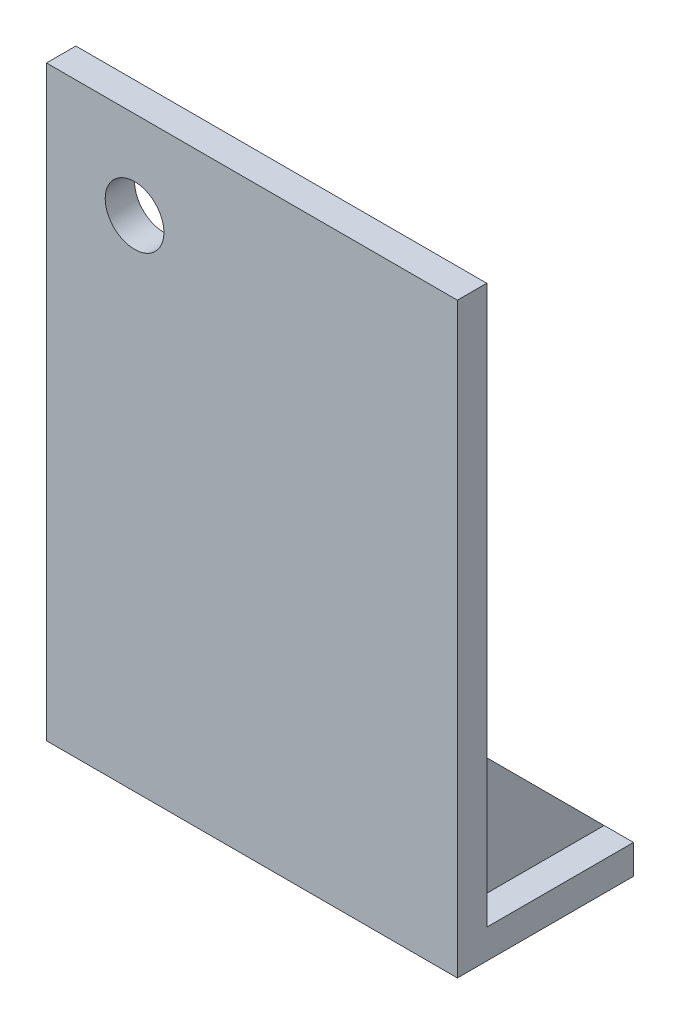
SolidWorks part; units mm, degrees
ref_plane "Front Plane" through (0, 0, 0) normal (0, 0, 1) x (1, 0, 0)
ref_plane "Top Plane" through (0, 0, 0) normal (0, 1, 0) x (1, 0, 0)
ref_plane "Right Plane" through (0, 0, 0) normal (1, 0, 0) x (0, 0, -1)
sketch "Sketch1" plane through (0, 0, 0) normal (0, 0, 1) x (1, 0, 0)
  line L0 (0, -15) -> (6.6093, -15) construction
  line L1 (5, 0) -> (70, 0)
  line L2 (0, -5) -> (0, -25)
  line L3 (5, -30) -> (40, -30)
  line L4 (70, 0) -> (70, -30)
  line L6 (70, -30) -> (70, -95)
  line L7 (70, -95) -> (40, -95)
  line L8 (40, -30) -> (40, -95)
  arc A1 (5, 0) -> (0, -5) centre (5, -5) ccw
  arc A2 (5, -30) -> (0, -25) centre (5, -25) cw
  dimension "D5" = 10
  dimension "D1" = 30
  dimension "D2" = 70
  dimension "D3" = 30
  dimension "D4" = 65
extrude "Boss-Extrude1" add sketch "Sketch1" along normal blind 5 contours L1 L4 L6 L7 L8 L3 A2 L2 A1
ref_plane "Plane1" through (55, 0, 0) normal (-1, 0, 0) x (0, 0, 1)
mirror "Mirror4" about plane through (55, 0, 0) normal (-1, 0, 0) of "Boss-Extrude1"
sketch "Sketch9" plane through (0, 0, 0) normal (0, 0, -1) x (-1, 0, 0)
  line L0 (-110, -5) -> (-110, -25) construction
  line L1 (-5, 0) -> (-105, 0) construction
  circle A0 centre (-95, -15) radius 5
  dimension "D1" = 10
  dimension "D2" = 15
  dimension "D3" = 15
extrude "Cut-Extrude4" cut sketch "Sketch9" against normal blind 10 contours A0
sketch "Sketch10" plane through (0, 0, 0) normal (0, 0, -1) x (-1, 0, 0)
  line L1 (-40, -30) -> (5.0273, -30)
  line L2 (-40, -30) -> (-40, 1.5058)
  line L3 (-40, 1.5058) -> (5.0273, 1.5058)
  line L4 (5.0273, -30) -> (5.0273, 1.5058)
extrude "Cut-Extrude5" cut sketch "Sketch10" against normal blind 10
sketch "Sketch11" plane through (0, 0, 0) normal (0, 0, -1) x (-1, 0, 0)
  line L0 (-110, -5) -> (-110, -25) construction
  line L1 (-40, 0) -> (-110, 0)
  line L2 (-40, 0) -> (-40, -95)
  line L3 (-40, -95) -> (-110, -95)
  line L4 (-110, 0) -> (-110, -95)
  line L5 (-70, -95) -> (-40, -95) construction
extrude "Boss-Extrude2" add sketch "Sketch11" against normal blind 5
sketch "Sketch12" plane through (0, 0, 0) normal (0, 0, -1) x (-1, 0, 0)
  line L0 (-40, 0) -> (-40, -95) construction
  line L2 (-40, 0) -> (-110, 0) construction
  circle A0 centre (-55, -15) radius 5
  dimension "D1" = 10
  dimension "D2" = 15
  dimension "D3" = 15
extrude "Cut-Extrude6" cut sketch "Sketch12" against normal blind 5
sketch "Sketch13" plane through (0, -95, 0) normal (0, -1, 0) x (1, 0, 0)
  line L0 (40, 5) -> (40, 0) construction
  line L1 (110, 5) -> (40, 5)
  line L2 (110, 5) -> (110, -25)
  line L3 (110, -25) -> (40, -25)
  line L4 (40, 5) -> (40, -25)
  dimension "D1" = 30
extrude "Boss-Extrude3" add sketch "Sketch13" along normal blind 5
ref_plane "Plane2" through (100, 0, 0) normal (1, 0, 0) x (0, 0, -1)
sketch "Sketch14" plane through (100, 0, 0) normal (1, 0, 0) x (0, 0, -1)
  line L0 (0, -70) -> (25, -95)
  line L1 (0, 0) -> (0, -95) construction
  line L2 (25, -95) -> (0, -95)
  line L3 (0, -95) -> (0, -70)
extrude "Boss-Extrude4" add sketch "Sketch14" along normal blind 5
